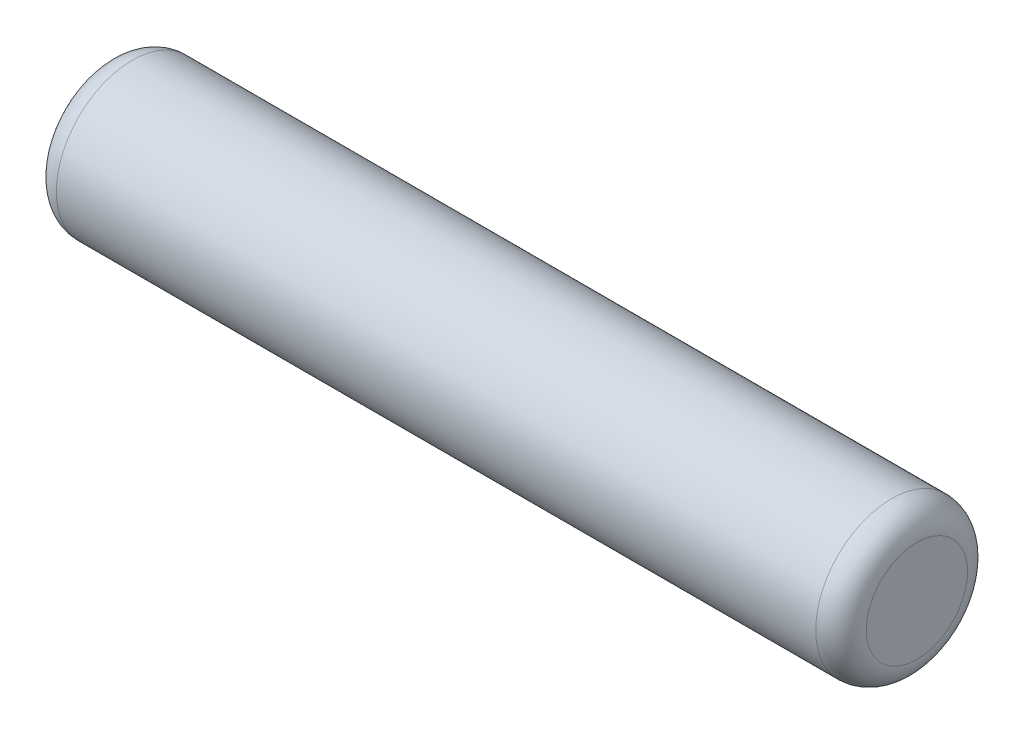
SolidWorks part; units mm, degrees
material "Cast Alloy Steel"
ref_plane "Front Plane" through (0, 0, 0) normal (0, 0, 1) x (1, 0, 0)
ref_plane "Top Plane" through (0, 0, 0) normal (0, 1, 0) x (1, 0, 0)
ref_plane "Right Plane" through (0, 0, 0) normal (1, 0, 0) x (0, 0, -1)
sketch "Sketch1" plane through (0, 0, 0) normal (1, 0, 0) x (0, 0, -1)
  circle A0 centre (0, 0) radius 1.5
  dimension "D1" = 3
extrude "Boss-Extrude1" add sketch "Sketch1" along normal blind 16
fillet "Fillet1" radius 0.5 2 edges at (16, 0, -1.5) (0, 0, -1.5)
